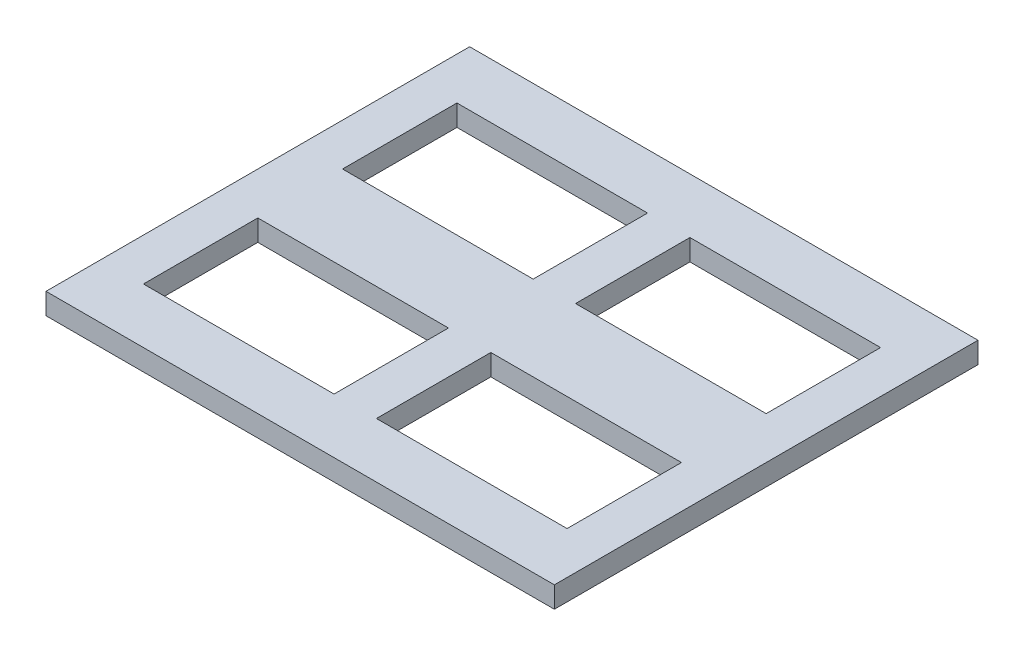
SolidWorks part; units mm, degrees
ref_plane "Front Plane" through (0, 0, 0) normal (0, 0, 1) x (1, 0, 0)
ref_plane "Top Plane" through (0, 0, 0) normal (0, 1, 0) x (1, 0, 0)
ref_plane "Right Plane" through (0, 0, 0) normal (1, 0, 0) x (0, 0, -1)
sketch "Sketch1" plane through (0, 0, 0) normal (0, 1, 0) x (1, 0, 0)
  line L0 (0, 60.2146) -> (0, -77.4091) construction
  line L1 (-60, 50) -> (60, 50)
  line L2 (-60, 50) -> (-60, -50)
  line L3 (-60, -50) -> (60, -50)
  line L4 (60, 50) -> (60, -50)
  line L5 (-60, 50) -> (60, -50) construction
  line L6 (-60, -50) -> (60, 50) construction
  line L7 (-50, 37) -> (-5, 37)
  line L8 (-50, 37) -> (-50, 10)
  line L9 (-50, 10) -> (-5, 10)
  line L10 (-5, 37) -> (-5, 10)
  line L11 (-50, 37) -> (-5, 10) construction
  line L12 (-50, 10) -> (-5, 37) construction
  line L13 (50, 10) -> (5, 37) construction
  line L14 (50, 37) -> (5, 10) construction
  line L15 (5, 37) -> (5, 10)
  line L16 (50, 10) -> (5, 10)
  line L17 (50, 37) -> (50, 10)
  line L18 (50, 37) -> (5, 37)
  line L19 (-79.0266, 0) -> (92.377, 0) construction
  line L20 (-50, -10) -> (-5, -37) construction
  line L21 (-50, -37) -> (-5, -10) construction
  line L22 (-5, -37) -> (-5, -10)
  line L23 (-50, -10) -> (-5, -10)
  line L24 (-50, -37) -> (-50, -10)
  line L25 (-50, -37) -> (-5, -37)
  line L26 (50, -37) -> (5, -10) construction
  line L27 (50, -10) -> (5, -37) construction
  line L28 (50, -37) -> (5, -37)
  line L29 (50, -37) -> (50, -10)
  line L30 (50, -10) -> (5, -10)
  line L31 (5, -37) -> (5, -10)
  point P4 (0, 0)
  point P11 (-27.5, 23.5)
  point P19 (27.5, 23.5)
  point P24 (-27.5, -23.5)
  point P29 (27.5, -23.5)
  dimension "D1" = 100
  dimension "D2" = 120
  dimension "D3" = 27
  dimension "D4" = 45
  dimension "D5" = 10
  dimension "D6" = 20
extrude "Boss-Extrude1" add sketch "Sketch1" along normal blind 5
